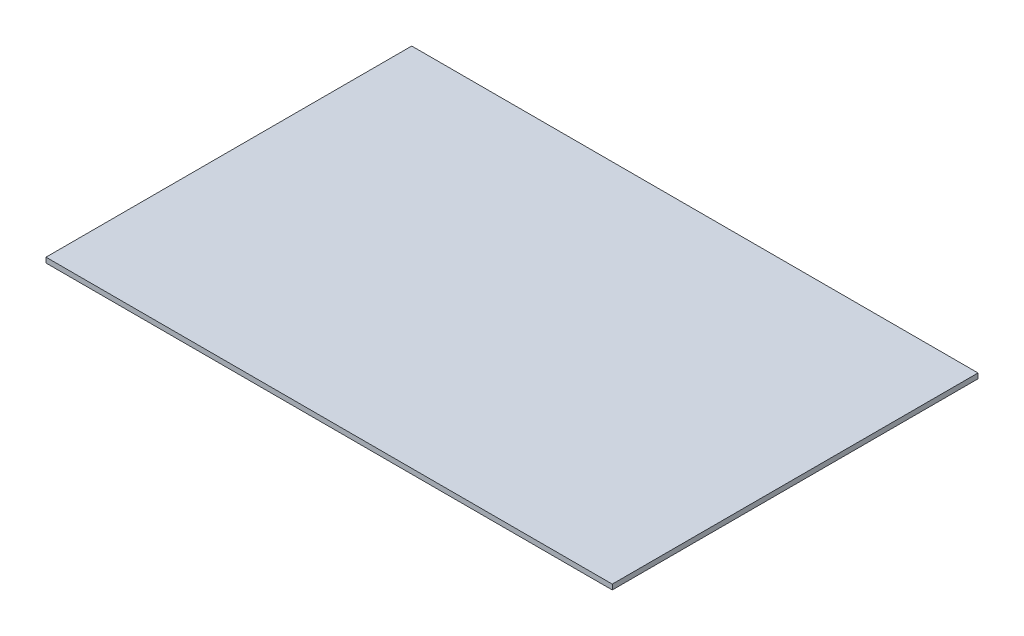
SolidWorks part; units mm, degrees
ref_plane "Front Plane" through (0, 0, 0) normal (0, 0, 1) x (1, 0, 0)
ref_plane "Top Plane" through (0, 0, 0) normal (0, 1, 0) x (1, 0, 0)
ref_plane "Right Plane" through (0, 0, 0) normal (1, 0, 0) x (0, 0, -1)
sketch "Sketch1" plane through (0, 0, 0) normal (0, 1, 0) x (1, 0, 0)
  line L1 (0, 0) -> (609.6, 0)
  line L2 (0, 0) -> (0, 393.7)
  line L3 (0, 393.7) -> (609.6, 393.7)
  line L4 (609.6, 0) -> (609.6, 393.7)
  dimension "D1" = 393.7
  dimension "D2" = 609.6
extrude "Boss-Extrude1" add sketch "Sketch1" along normal blind 5.5
